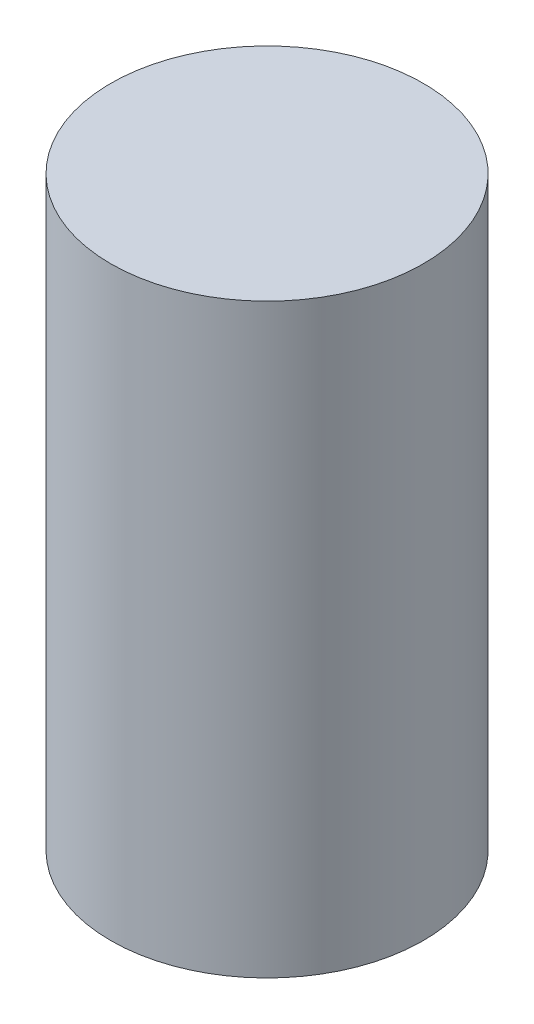
SolidWorks part; units mm, degrees
ref_plane "Front Plane" through (0, 0, 0) normal (0, 0, 1) x (1, 0, 0)
ref_plane "Top Plane" through (0, 0, 0) normal (0, 1, 0) x (1, 0, 0)
ref_plane "Right Plane" through (0, 0, 0) normal (1, 0, 0) x (0, 0, -1)
sketch "Sketch2" plane through (0, 0, 0) normal (0, 1, 0) x (1, 0, 0)
  circle A0 centre (0, 0) radius 2
extrude "Boss-Extrude1" add sketch "Sketch2" along normal blind 7.5
